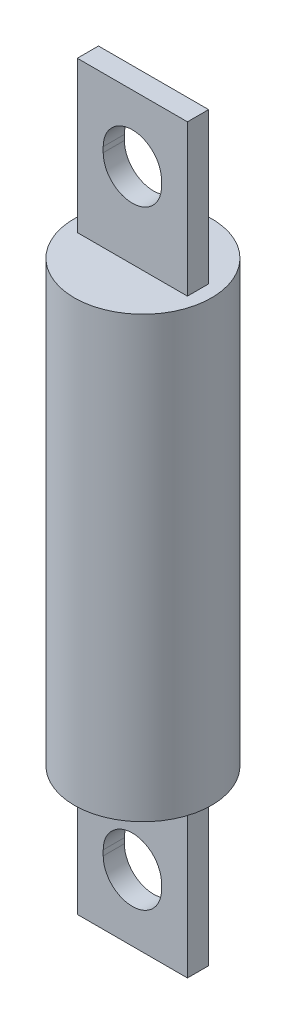
SolidWorks part; units mm, degrees
ref_plane "X-Y Datum" through (0, 0, 0) normal (0, 0, 1) x (1, 0, 0)
ref_plane "X-Z Datum" through (0, 0, 0) normal (0, 1, 0) x (1, 0, 0)
ref_plane "Y-Z Datum" through (0, 0, 0) normal (1, 0, 0) x (0, 0, -1)
sketch "Sketch1" plane through (0, 0, 0) normal (0, 1, 0) x (1, 0, 0)
  circle A0 centre (0, 0) radius 10.287
extrude "Boss-Extrude1" add sketch "Sketch1" along normal blind 65.8876
sketch "Sketch2" plane through (0, 65.8876, 0) normal (0, 1, 0) x (1, 0, 0)
  line L1 (-8.255, -1.5875) -> (8.255, -1.5875)
  line L2 (-8.255, -1.5875) -> (-8.255, 1.5875)
  line L3 (-8.255, 1.5875) -> (8.255, 1.5875)
  line L4 (8.255, -1.5875) -> (8.255, 1.5875)
  line L5 (-8.255, -1.5875) -> (8.255, 1.5875) construction
  line L6 (-8.255, 1.5875) -> (8.255, -1.5875) construction
  point P0 (0, 0)
extrude "Boss-Extrude2" add sketch "Sketch2" along normal blind 22.6314
ref_plane "Plane1" through (0, 32.9438, 0) normal (0, 1, 0) x (1, 0, 0)
sketch "Sketch3" plane through (0, 0, 1.5875) normal (0, 0, 1) x (1, 0, 0)
  line L0 (0, 32.9438) -> (0, 78.1939) construction
  line L1 (11.3157, 32.9438) -> (-11.3157, 32.9438) construction
  line L2 (0, 32.9438) -> (0, 78.9851) construction
  line L3 (-4.3688, 78.9851) -> (-4.3688, 78.1939)
  line L4 (4.3688, 78.9851) -> (4.3688, 78.1939)
  arc A0 (4.3688, 78.9851) -> (-4.3688, 78.9851) centre (0, 78.9851) ccw
  arc A1 (-4.3688, 78.1939) -> (4.3688, 78.1939) centre (0, 78.1939) ccw
extrude "Cut-Extrude1" cut sketch "Sketch3" against normal through all
mirror "Mirror2" about plane through (0, 32.9438, 0) normal (0, 1, 0) of "Cut-Extrude1", "Boss-Extrude2"
